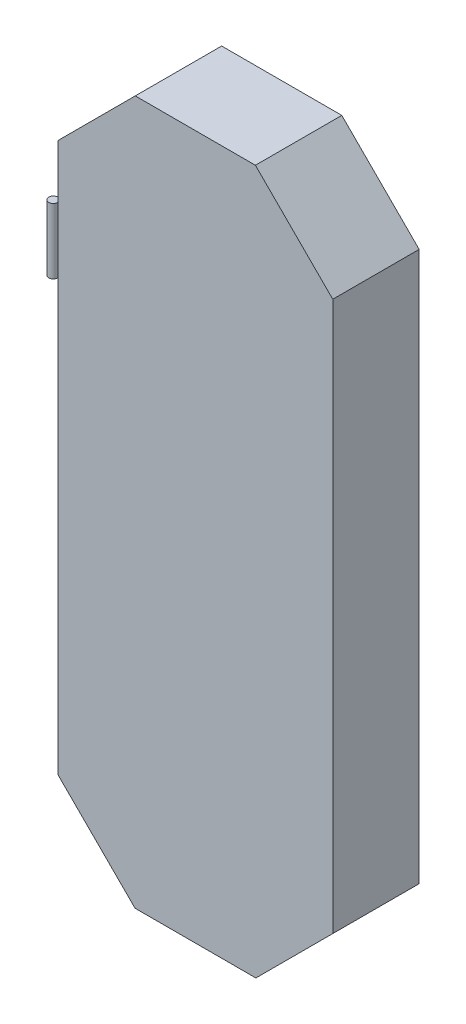
SolidWorks part; units mm, degrees
ref_plane "Спереди" through (0, 0, 0) normal (0, 0, 1) x (1, 0, 0)
ref_plane "Сверху" through (0, 0, 0) normal (0, 1, 0) x (1, 0, 0)
ref_plane "Справа" through (0, 0, 0) normal (1, 0, 0) x (0, 0, -1)
sketch "Эскиз1" plane through (0, 0, 0) normal (0, 0, 1) x (1, 0, 0)
  line L0 (105.0829, 581.7221) -> (45.979, 640.8259)
  line L1 (45.979, 640.8259) -> (-45.8132, 640.8259)
  line L2 (-45.8132, 640.8259) -> (-104.9171, 581.7221)
  line L3 (-104.9171, 581.7221) -> (-104.9171, 162.2129)
  line L4 (-104.9171, 162.2129) -> (-45.9732, 103.269)
  line L5 (-45.9732, 103.269) -> (46.3268, 103.269)
  line L6 (46.3268, 103.269) -> (105.0829, 162.0251)
  line L7 (105.0829, 162.0251) -> (105.0829, 581.7221)
  line L8 (0.0829, 640.8259) -> (0.0829, 703.4762) construction
  dimension "D1" = 105
  dimension "D2" = 105
extrude "Вытянуть1" add sketch "Эскиз1" along normal blind 66
ref_plane "Plane1" through (0, 490.8259, 0) normal (0, 1, 0) x (1, 0, 0)
sketch "Sketch1" plane through (0, 490.8259, 0) normal (0, 1, 0) x (1, 0, 0)
  line L0 (-104.9171, -66) -> (-157.3178, -66) construction
  line L1 (-104.9171, 0) -> (-104.9171, 70.7003) construction
  circle A0 centre (-108.4171, -66) radius 3.5
extrude "Boss-Extrude1" add sketch "Sketch1" along normal blind 50 separate body
sketch "Sketch2" plane through (0, 0, 0) normal (0, 0, -1) x (-1, 0, 0)
  line L0 (-45.979, 640.8259) -> (45.8132, 640.8259) construction
  line L1 (-0.0829, 640.8259) -> (-0.0829, 333.1673) construction
  circle A0 centre (-0.0829, 539.8259) radius 42
  dimension "D1" = 101
extrude "Boss-Extrude2" add sketch "Sketch2" along normal blind 21
sketch "Sketch3" plane through (0, 0, -21) normal (0, 0, -1) x (-1, 0, 0)
  circle A0 centre (-0.0829, 539.8259) radius 15
extrude "Cut-Extrude1" cut sketch "Sketch3" against normal blind 20
